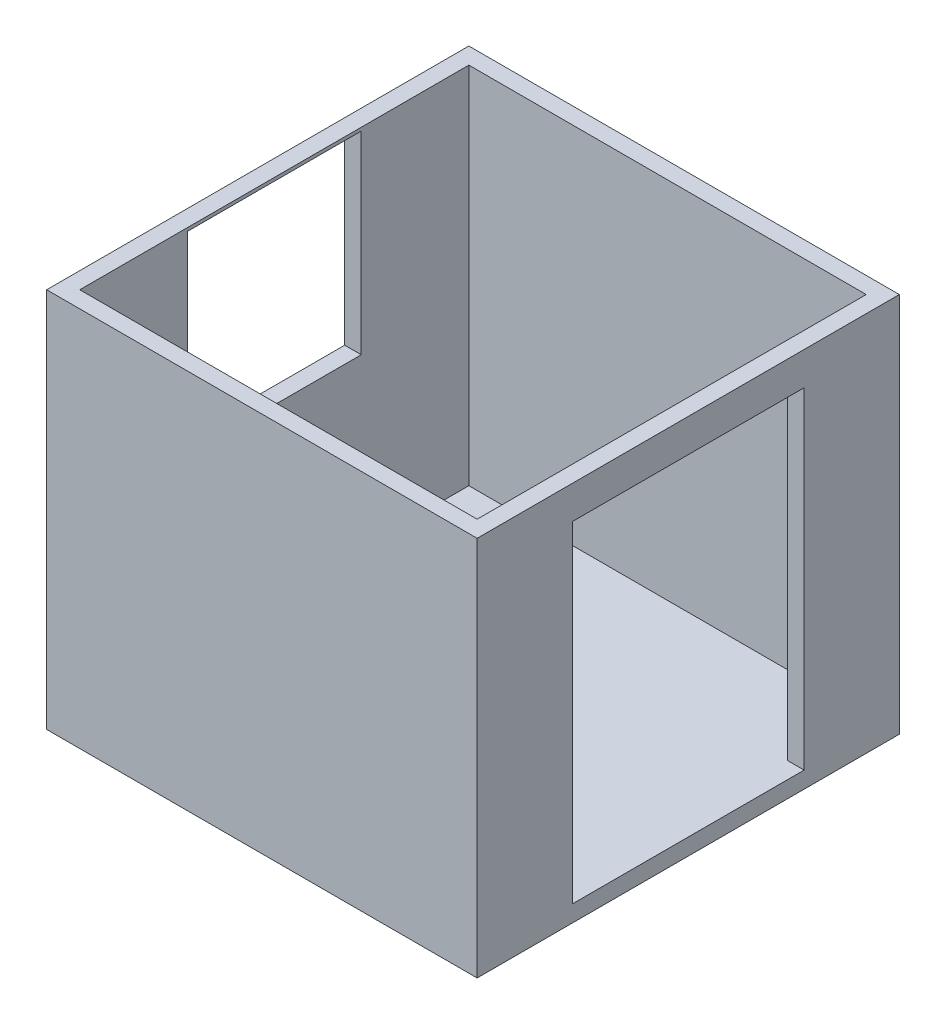
SolidWorks part; units mm, degrees
ref_plane "정면" through (0, 0, 0) normal (0, 0, 1) x (1, 0, 0)
ref_plane "윗면" through (0, 0, 0) normal (0, 1, 0) x (1, 0, 0)
ref_plane "우측면" through (0, 0, 0) normal (1, 0, 0) x (0, 0, -1)
sketch "스케치1" plane through (0, 0, 0) normal (0, 1, 0) x (1, 0, 0)
  line L0 (-1300, 1275) -> (-1300, -1275)
  line L1 (-1200, 1175) -> (1200, 1175)
  line L2 (-1200, 1175) -> (-1200, -1175)
  line L3 (-1200, -1175) -> (1200, -1175)
  line L4 (1200, 1175) -> (1200, -1175)
  line L5 (-1200, 1175) -> (1200, -1175) construction
  line L6 (-1200, -1175) -> (1200, 1175) construction
  line L7 (-1300, -1275) -> (1300, -1275)
  line L8 (1300, 1275) -> (1300, -1275)
  line L9 (-1300, 1275) -> (1300, 1275)
  point P0 (0, 0)
  dimension "D1" = 2350
  dimension "D2" = 2400
  dimension "D3" = 100
extrude "벽" add sketch "스케치1" along normal blind 2200
sketch "스케치2" plane through (0, 0, 0) normal (0, -1, 0) x (1, 0, 0)
  line L1 (-1300, 1275) -> (1300, 1275)
  line L2 (-1300, 1275) -> (-1300, -1275)
  line L3 (-1300, -1275) -> (1300, -1275)
  line L4 (1300, 1275) -> (1300, -1275)
  line L5 (-1300, 1275) -> (1300, -1275) construction
  line L6 (-1300, -1275) -> (1300, 1275) construction
  point P0 (0, 0)
extrude "바닥" add sketch "스케치2" along normal blind 100
sketch "스케치5" plane through (1300, 0, 0) normal (1, 0, 0) x (0, 0, -1)
  line L0 (-1175, 0) -> (1175, 0) construction
  line L1 (-700, 2000) -> (700, 2000)
  line L2 (-700, 2000) -> (-700, 0)
  line L3 (-700, 0) -> (700, 0)
  line L4 (700, 2000) -> (700, 0)
  line L5 (-700, 2000) -> (700, 0) construction
  line L6 (-700, 0) -> (700, 2000) construction
  line L7 (0, 0) -> (0, 1000) construction
  point P0 (0, 1000)
  dimension "D1" = 2000
  dimension "D2" = 1400
extrude "문" cut sketch "스케치5" against normal up to next
sketch "스케치6" plane through (-1300, 0, 0) normal (-1, 0, 0) x (0, 0, 1)
  line L0 (0, 0) -> (0, 1595) construction
  line L1 (-525, 2180) -> (525, 2180)
  line L2 (-525, 2180) -> (-525, 1010)
  line L3 (-525, 1010) -> (525, 1010)
  line L4 (525, 2180) -> (525, 1010)
  line L5 (-525, 2180) -> (525, 1010) construction
  line L6 (-525, 1010) -> (525, 2180) construction
  line L7 (-1275, 2200) -> (1275, 2200) construction
  point P0 (0, 1595)
  dimension "D1" = 20
  dimension "D2" = 1050
  dimension "D3" = 1170
extrude "창문" cut sketch "스케치6" against normal up to next contours L4 L1 L2 L3
